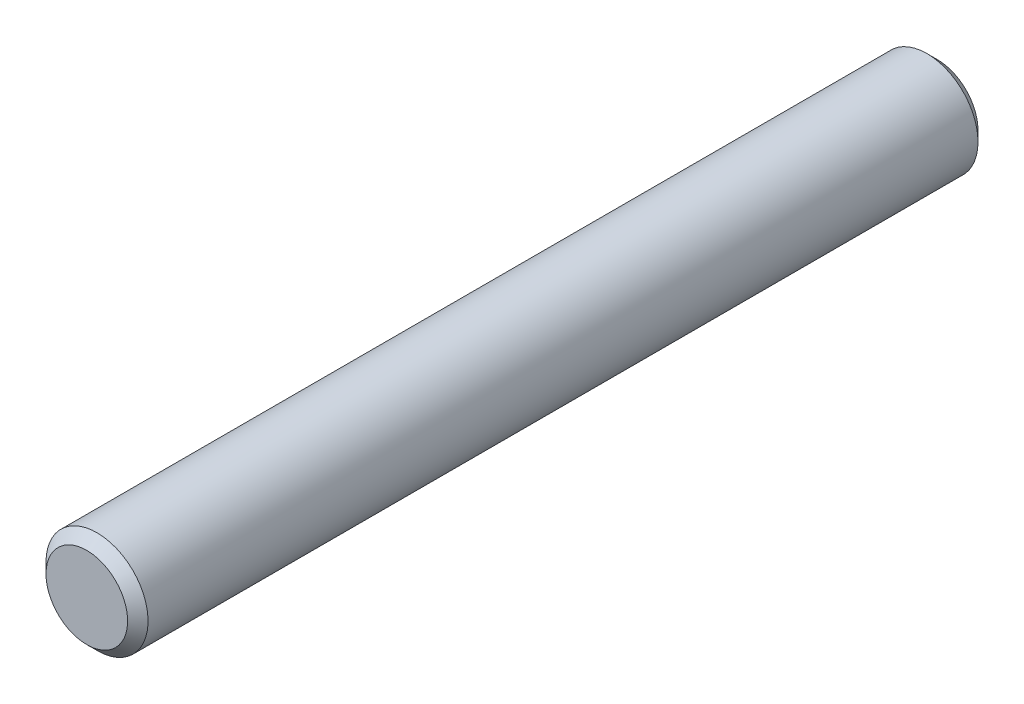
SolidWorks part; units mm, degrees
material "1023 Carbon Steel Sheet (SS)"
ref_plane "Front" through (0, 0, 0) normal (0, 0, 1) x (1, 0, 0)
ref_plane "Top" through (0, 0, 0) normal (0, 1, 0) x (1, 0, 0)
ref_plane "Right" through (0, 0, 0) normal (1, 0, 0) x (0, 0, -1)
sketch "Sketch1" plane through (0, 0, 0) normal (0, 0, 1) x (1, 0, 0)
  circle A0 centre (0, 0) radius 4.7625
  dimension "Diameter" = 9.525
sketch "Sketch2" plane through (0, 0, 0) normal (1, 0, 0) x (0, 0, -1)
  line L0 (-39.6875, 0) -> (39.6875, 0) construction
  line L1 (11.1125, 4.7625) -> (11.1125, -4.7625) construction
  line L2 (55, 0) -> (-55, 0) construction
  line L3 (-11.1125, 4.7625) -> (-11.1125, -4.7625) construction
  line L4 (-39.6875, 4.7625) -> (-39.6875, -4.7625) construction
  line L5 (39.6875, 4.7625) -> (39.6875, -4.7625) construction
  point P3 (11.1125, 0)
  point P8 (0, 0)
  point P9 (-11.1125, 0)
  point P15 (-39.6875, 0)
  point P18 (39.6875, 0)
  dimension "D1" = 9.525
  dimension "Length" = 79.375
  dimension "D2" = 50.8
  dimension "D3" = 50.8
sketch "Sketch3" plane through (0, 0, 0) normal (0, 0, 1) x (1, 0, 0)
  circle A0 centre (0, 0) radius 4.7625
  dimension "D1" = 9.525
extrude "Boss-Extrude1" add sketch "Sketch3" along normal mid plane 79.375
chamfer "Chamfer1" distance 0.9525 angle 45 2 edges at (4.7625, 0, -39.6875) (4.7625, 0, 39.6875)
equation "\"D1@Sketch3\" = \"Diameter@Sketch1\""
equation "\"D1@Boss-Extrude1\" = \"Length@Sketch2\""
equation "\"D1@Chamfer1\" = \"Diameter@Sketch1\" * .1"
equation "\"D1@Sketch2\" = \"Diameter@Sketch1\""
